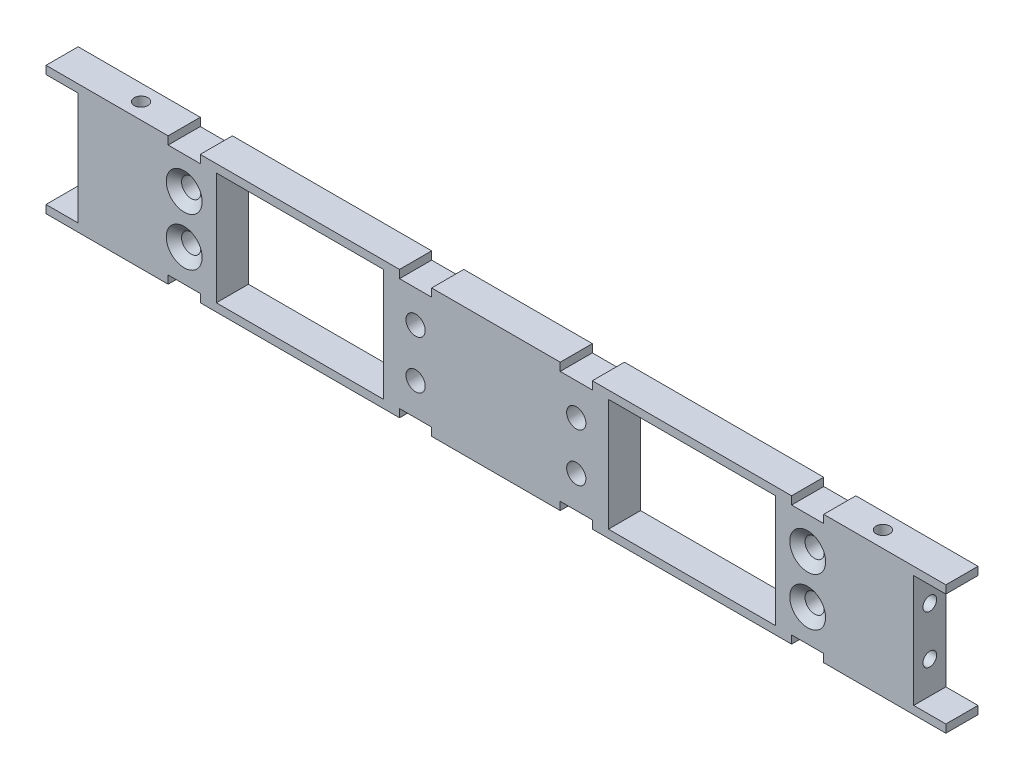
SolidWorks part; units mm, degrees
material "6061-T6 (SS)"
ref_plane "Front Plane" through (0, 0, 0) normal (0, 0, 1) x (1, 0, 0)
ref_plane "Top Plane" through (0, 0, 0) normal (0, 1, 0) x (1, 0, 0)
ref_plane "Right Plane" through (0, 0, 0) normal (1, 0, 0) x (0, 0, -1)
sketch "Sketch1" plane through (0, 0, 0) normal (0, 0, 1) x (1, 0, 0)
  line L0 (0, 12.7) -> (0, -12.7) construction
  line L1 (-88.9, 12.7) -> (88.9, 12.7)
  line L2 (-88.9, 12.7) -> (-88.9, 11.1125)
  line L3 (-88.9, -12.7) -> (88.9, -12.7)
  line L4 (88.9, 12.7) -> (88.9, 11.1125)
  line L7 (-88.9, 11.1125) -> (-82.55, 11.1125)
  line L8 (88.9, -11.1125) -> (82.55, -11.1125)
  line L9 (-88.9, -11.1125) -> (-82.55, -11.1125)
  line L10 (-82.55, 11.1125) -> (-82.55, -11.1125)
  line L11 (-88.9, -11.1125) -> (-88.9, -12.7)
  line L12 (82.55, 11.1125) -> (82.55, -11.1125)
  line L13 (88.9, 11.1125) -> (82.55, 11.1125)
  line L14 (88.9, -11.1125) -> (88.9, -12.7)
  point P0 (0, 0)
  dimension "D1" = 177.8
  dimension "D2" = 25.4
  dimension "D3" = 6.35
  dimension "D4" = 1.5875
  dimension "D5" = 1.5875
extrude "Boss-Extrude1" add sketch "Sketch1" along normal blind 6.35
ref_plane "Plane1" through (0, 0, 0) normal (1, 0, 0) x (0, 0, -1)
hole_wizard "Tap Drill for #6-32 Tap1" positions "Sketch3" profile "Sketch4" hole size "#6-32" standard "ANSI Inch"
sketch "Sketch3" plane through (-82.55, 0, 0) normal (-1, 0, 0) x (0, 0, 1)
  line L0 (6.35, 11.1125) -> (0, 11.1125) construction
  line L1 (0, 11.1125) -> (0, -11.1125) construction
  point P0 (3.175, 4.7625)
  point P2 (3.175, -4.7625)
  dimension "D1" = 6.35
  dimension "D2" = 6.35
  dimension "D3" = 3.175
  dimension "D4" = 3.175
sketch "Sketch4" plane through (-82.55, 4.7625, 3.175) normal (0, 1, 0) x (0, 0, 1)
  line L0 (0, 0) -> (0, 13.5127)
  line L1 (0, 13.5127) -> (1.3525, 12.7)
  line L2 (1.3525, 12.7) -> (1.3525, 0)
  line L5 (1.3525, 0) -> (0, 0)
  line L10 (0, 13.5127) -> (-1.3526, 12.7) construction
  line L11 (0, -6.35) -> (0, 107.95) construction
  dimension "Hole Dia." = 2.7051
  dimension "Hole Depth" = 12.7
  dimension "Drill Angle" = 118
mirror "Mirror1" about plane through (0, 0, 0) normal (1, 0, 0) of "Tap Drill for #6-32 Tap1"
hole_wizard "Tap Drill for #6-32 Tap2" positions "Sketch6" profile "Sketch5" hole size "#6-32" standard "ANSI Inch"
sketch "Sketch6" plane through (0, 12.7, 0) normal (0, 1, 0) x (1, 0, 0)
  line L0 (-88.9, -6.35) -> (-88.9, 0) construction
  point P0 (-73.2896, -3.175)
  point P9 (-88.9, -3.175)
  dimension "D1" = 15.6104
sketch "Sketch5" plane through (-73.2896, 12.7, 3.175) normal (1, 0, 0) x (0, 0, 1)
  line L0 (0, 0) -> (0, 7.1627)
  line L1 (0, 7.1627) -> (1.3525, 6.35)
  line L2 (1.3525, 6.35) -> (1.3525, 0)
  line L5 (1.3525, 0) -> (0, 0)
  line L10 (0, 7.1627) -> (-1.3526, 6.35) construction
  line L11 (0, -6.35) -> (0, 107.95) construction
  dimension "Hole Dia." = 2.7051
  dimension "Hole Depth" = 6.35
  dimension "Drill Angle" = 118
ref_plane "Plane2" through (0, 0, 0) normal (0, -1, 0) x (-1, 0, 0)
mirror "Mirror2" about plane through (0, 0, 0) normal (1, 0, 0) of "Tap Drill for #6-32 Tap2"
mirror "Mirror3" about plane through (0, 0, 0) normal (0, -1, 0) of "Mirror2", "Tap Drill for #6-32 Tap2"
sketch "Sketch7" plane through (0, 0, 6.35) normal (0, 0, 1) x (1, 0, 0)
  line L0 (-64.77, 11.1125) -> (-58.42, 11.1125) construction
  line L1 (-64.77, 11.1125) -> (-64.77, 12.7) construction
  line L2 (-58.42, 11.1125) -> (-58.42, 12.7) construction
  line L3 (-64.77, 12.7) -> (-58.42, 12.7) construction
  line L4 (-64.77, -11.1125) -> (-58.42, -11.1125) construction
  line L5 (-64.77, -12.7) -> (-64.77, -11.1125) construction
  line L6 (-88.9, -12.7) -> (88.9, -12.7) construction
  line L7 (-58.42, -12.7) -> (-58.42, -11.1125) construction
  line L8 (58.42, -11.1125) -> (58.42, -12.7) construction
  line L9 (64.77, -11.1125) -> (58.42, -11.1125) construction
  line L10 (64.77, -11.1125) -> (64.77, -12.7) construction
  line L11 (58.42, 12.7) -> (58.42, 11.1125) construction
  line L12 (64.77, 11.1125) -> (58.42, 11.1125) construction
  line L13 (64.77, 12.7) -> (64.77, 11.1125) construction
  line L14 (64.77, 12.7) -> (58.42, 12.7) construction
  line L15 (-64.77, 11.1125) -> (-58.42, 11.1125)
  line L16 (-64.77, 11.1125) -> (-64.77, 12.7)
  line L17 (-58.42, 11.1125) -> (-58.42, 12.7)
  line L18 (-64.77, 12.7) -> (-58.42, 12.7)
  line L19 (-64.77, -11.1125) -> (-58.42, -11.1125)
  line L20 (-64.77, -12.7) -> (-64.77, -11.1125)
  line L21 (-64.77, -12.7) -> (-58.42, -12.7)
  line L22 (-58.42, -12.7) -> (-58.42, -11.1125)
  line L23 (58.42, -11.1125) -> (58.42, -12.7)
  line L24 (64.77, -11.1125) -> (58.42, -11.1125)
  line L25 (64.77, -11.1125) -> (64.77, -12.7)
  line L26 (58.42, 12.7) -> (58.42, 11.1125)
  line L27 (64.77, 11.1125) -> (58.42, 11.1125)
  line L28 (64.77, 12.7) -> (64.77, 11.1125)
  line L29 (64.77, 12.7) -> (58.42, 12.7)
  line L30 (58.42, -12.7) -> (64.77, -12.7)
extrude "Cut-Extrude1" cut sketch "Sketch7" against normal through all
sketch "Sketch10" plane through (0, 0, 0) normal (0, 0, -1) x (-1, 0, 0)
  line L0 (-19.05, 11.1125) -> (-19.05, 12.7) construction
  line L1 (-19.05, 11.1125) -> (-12.7, 11.1125) construction
  line L2 (-12.7, 11.1125) -> (-12.7, 12.7) construction
  line L3 (12.7, 11.1125) -> (19.05, 11.1125) construction
  line L4 (19.05, 11.1125) -> (19.05, 12.7) construction
  line L5 (12.7, 11.1125) -> (12.7, 12.7) construction
  line L6 (58.42, 12.7) -> (-58.42, 12.7) construction
  line L7 (-19.05, -11.1125) -> (-12.7, -11.1125) construction
  line L8 (-19.05, -12.7) -> (-19.05, -11.1125) construction
  line L9 (-12.7, -12.7) -> (-12.7, -11.1125) construction
  line L10 (58.42, -12.7) -> (-58.42, -12.7) construction
  line L11 (19.05, -12.7) -> (19.05, -11.1125) construction
  line L12 (12.7, -11.1125) -> (19.05, -11.1125) construction
  line L13 (12.7, -12.7) -> (12.7, -11.1125) construction
  line L14 (-19.05, 11.1125) -> (-19.05, 12.7)
  line L15 (-19.05, 11.1125) -> (-12.7, 11.1125)
  line L16 (-12.7, 11.1125) -> (-12.7, 12.7)
  line L17 (12.7, 11.1125) -> (19.05, 11.1125)
  line L18 (19.05, 11.1125) -> (19.05, 12.7)
  line L19 (12.7, 11.1125) -> (12.7, 12.7)
  line L20 (19.05, 12.7) -> (12.7, 12.7)
  line L21 (-19.05, -11.1125) -> (-12.7, -11.1125)
  line L22 (-19.05, -12.7) -> (-19.05, -11.1125)
  line L23 (-12.7, -12.7) -> (-12.7, -11.1125)
  line L24 (19.05, -12.7) -> (12.7, -12.7)
  line L25 (19.05, -12.7) -> (19.05, -11.1125)
  line L26 (12.7, -11.1125) -> (19.05, -11.1125)
  line L27 (12.7, -12.7) -> (12.7, -11.1125)
  line L28 (-12.7, 12.7) -> (-19.05, 12.7)
  line L29 (-12.7, -12.7) -> (-19.05, -12.7)
  line L30 (58.42, 12.7) -> (-58.42, 12.7) construction
  line L31 (-55.245, 11.1125) -> (-22.225, 11.1125)
  line L32 (-55.245, 11.1125) -> (-55.245, -11.1125)
  line L33 (-55.245, -11.1125) -> (-22.225, -11.1125)
  line L34 (-22.225, 11.1125) -> (-22.225, -11.1125)
  line L35 (22.225, -11.1125) -> (55.245, -11.1125)
  line L36 (22.225, -11.1125) -> (22.225, 11.1125)
  line L37 (22.225, 11.1125) -> (55.245, 11.1125)
  line L38 (55.245, -11.1125) -> (55.245, 11.1125)
  line L39 (58.42, 11.1125) -> (58.42, 12.7) construction
  dimension "D1" = 1.5875
  dimension "D2" = 1.5875
  dimension "D3" = 1.5875
  dimension "D4" = 1.5875
  dimension "D5" = 3.175
  dimension "D6" = 3.175
  dimension "D7" = 3.175
  dimension "D8" = 3.175
extrude "Cut-Extrude5" cut sketch "Sketch10" against normal through all
hole_wizard "CSK for #6 Flat Head Machine Screw (100)1" positions "Sketch9" profile "Sketch8" countersink size "#6" standard "ANSI Inch" end condition through all
sketch "Sketch9" plane through (0, 0, 6.35) normal (0, 0, 1) x (1, 0, 0)
  line L0 (-64.77, 11.1125) -> (-58.42, 11.1125) construction
  line L1 (-38.735, 12.7) -> (-38.735, -12.7) construction
  line L2 (-58.42, 12.7) -> (-19.05, 12.7) construction
  line L3 (-58.42, -12.7) -> (-19.05, -12.7) construction
  point P0 (-61.595, 4.7625)
  point P2 (-61.595, -4.7625)
  point P7 (-61.595, 11.1125)
  dimension "D1" = 7.9375
  dimension "D2" = 7.9375
sketch "Sketch8" plane through (-61.595, 4.7625, 6.35) normal (1, 0, 0) x (0, -1, 0)
  line L0 (0, 0) -> (0, 6.35)
  line L1 (0, 6.35) -> (1.8986, 6.35)
  line L2 (1.8986, 6.35) -> (1.8986, 1.38)
  line L3 (1.8986, 1.38) -> (3.5433, 0)
  line L5 (3.5433, 0) -> (0, 0)
  line L6 (-1.8986, 1.38) -> (-3.5433, 0) construction
  line L11 (0, -6.35) -> (0, 107.95) construction
  dimension "Thru Hole Dia." = 3.7973
  dimension "Thru Hole Depth" = 6.35
  dimension "Near C'Sink Dia." = 7.0866
  dimension "Near C'Sink Angle" = 100
hole_wizard "CSK for #6 Flat Head Machine Screw (100)2" positions "Sketch12" profile "Sketch11" countersink size "#6" standard "ANSI Inch" end condition through all
sketch "Sketch12" plane through (0, 0, 0) normal (0, 0, -1) x (-1, 0, 0)
  line L0 (12.7, 11.1125) -> (19.05, 11.1125) construction
  line L1 (12.7, 12.7) -> (-12.7, 12.7) construction
  line L2 (58.42, -12.7) -> (19.05, -12.7) construction
  point P0 (15.875, 4.7625)
  point P2 (15.875, -4.7625)
  point P7 (15.875, 11.1125)
  dimension "D1" = 7.9375
  dimension "D2" = 7.9375
sketch "Sketch11" plane through (-15.875, 4.7625, 0) normal (1, 0, 0) x (0, 1, 0)
  line L0 (0, 0) -> (0, 6.35)
  line L1 (0, 6.35) -> (1.8986, 6.35)
  line L2 (1.8986, 6.35) -> (1.8986, 1.38)
  line L3 (1.8986, 1.38) -> (3.5433, 0)
  line L5 (3.5433, 0) -> (0, 0)
  line L6 (-1.8986, 1.38) -> (-3.5433, 0) construction
  line L11 (0, -6.35) -> (0, 107.95) construction
  dimension "Thru Hole Dia." = 3.7973
  dimension "Thru Hole Depth" = 6.35
  dimension "Near C'Sink Dia." = 7.0866
  dimension "Near C'Sink Angle" = 100
mirror "Mirror5" about plane through (0, 0, 0) normal (1, 0, 0) of "CSK for #6 Flat Head Machine Screw (100)1", "CSK for #6 Flat Head Machine Screw (100)2"
